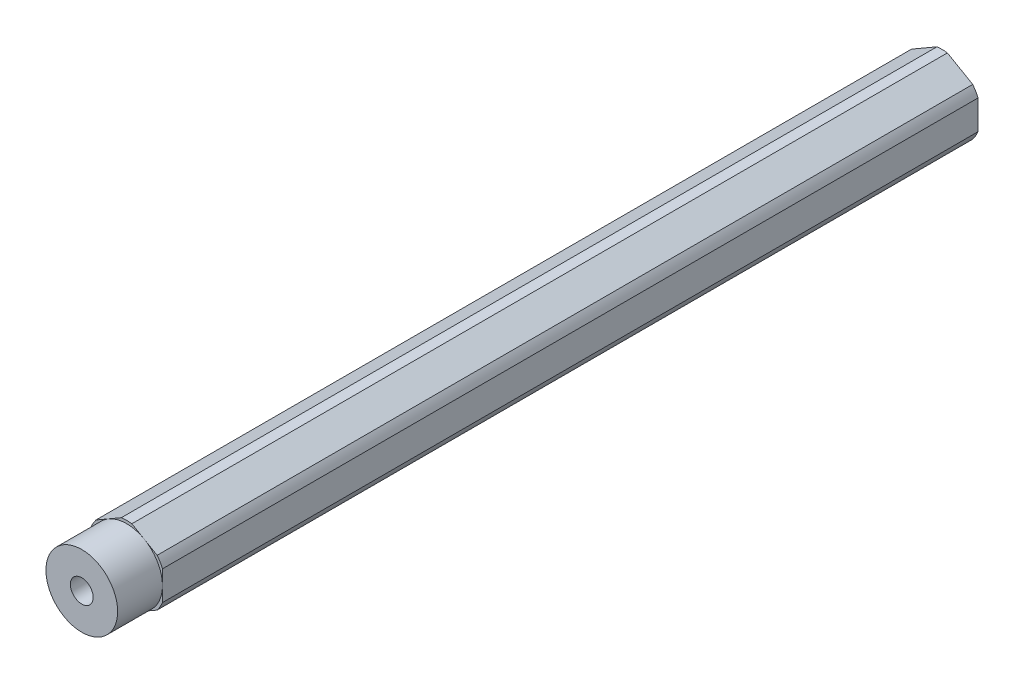
SolidWorks part; units mm, degrees
material "6061-T6 (SS)"
ref_plane "Front Plane" through (0, 0, 0) normal (0, 0, 1) x (1, 0, 0)
ref_plane "Top Plane" through (0, 0, 0) normal (0, 1, 0) x (1, 0, 0)
ref_plane "Right Plane" through (0, 0, 0) normal (1, 0, 0) x (0, 0, -1)
sketch "Sketch1" plane through (0, 0, 0) normal (0, 0, 1) x (1, 0, 0)
  line L1 (0, 7.3323) -> (-6.35, 3.6662)
  line L2 (-6.35, 3.6662) -> (-6.35, -3.6662)
  line L3 (-6.35, -3.6662) -> (0, -7.3323)
  line L4 (0, -7.3323) -> (6.35, -3.6662)
  line L5 (6.35, -3.6662) -> (6.35, 3.6662)
  line L6 (6.35, 3.6662) -> (0, 7.3323)
  circle A0 centre (0, 0) radius 6.35 construction
  circle A1 centre (0, 0) radius 6.858
  circle A2 centre (0, 0) radius 2.0193 construction
  dimension "D1" = 12.7
  dimension "D2" = 13.716
  dimension "D3" = 4.0386
extrude "Boss-Extrude1" add sketch "Sketch1" along normal mid plane 144.4625 contours L5 A1 L6 L1 L2 L3 L4
sketch "Sketch2" plane through (0, 0, 72.2313) normal (0, 0, 1) x (1, 0, 0)
  circle A0 centre (0, 0) radius 6.35
  circle A1 centre (0, 0) radius 2.0193
  dimension "D1" = 12.7
  dimension "D2" = 4.0386
extrude "Boss-Extrude2" add sketch "Sketch2" along normal blind 7.9375
hole_wizard "#10-32 Tapped Hole1" positions "Sketch3" profile "Sketch4" tap size "#10-32" standard "ANSI Inch" end condition through all
sketch "Sketch3" plane through (0, 0, -72.2313) normal (0, 0, -1) x (-1, 0, 0)
  point P0 (0, 0)
sketch "Sketch4" plane through (0, 0, -72.2313) normal (1, 0, 0) x (0, 1, 0)
  line L0 (0, 0) -> (0, 152.4)
  line L1 (0, 152.4) -> (2.0193, 152.4)
  line L2 (2.0193, 152.4) -> (2.0193, 0)
  line L5 (2.0193, 0) -> (0, 0)
  line L11 (0, -6.35) -> (0, 107.95) construction
  dimension "Thru Tap Drill Dia." = 4.0386
  dimension "Thru Tap Drill Depth" = 152.4
cosmetic thread "Hole Thread1" parameters "D2"=4.826
